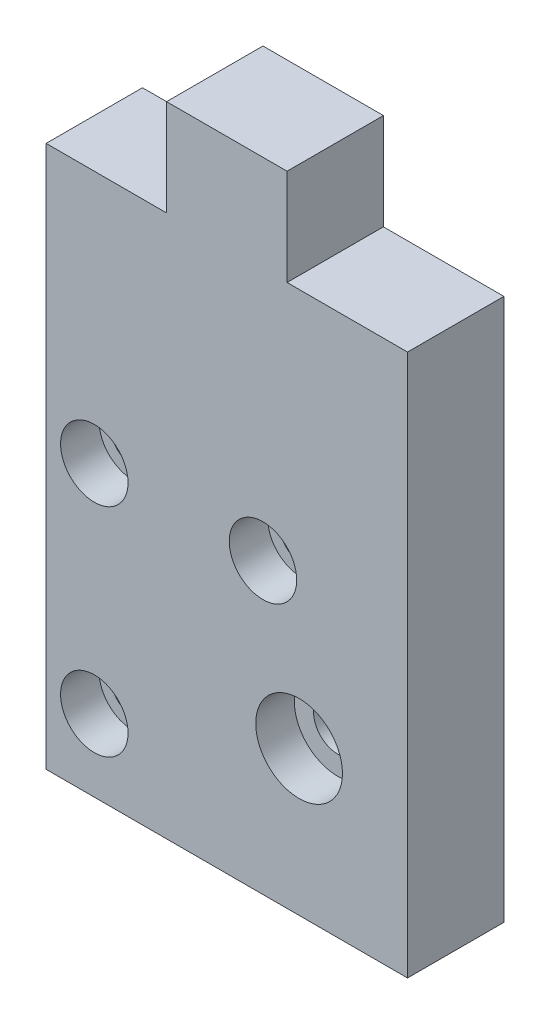
SolidWorks part; units mm, degrees
ref_plane "Front Plane" through (0, 0, 0) normal (0, 0, 1) x (1, 0, 0)
ref_plane "Top Plane" through (0, 0, 0) normal (0, 1, 0) x (1, 0, 0)
ref_plane "Right Plane" through (0, 0, 0) normal (1, 0, 0) x (0, 0, -1)
sketch "Sketch1" plane through (0, 0, 0) normal (0, 0, 1) x (1, 0, 0)
  line L0 (0, 57.15) -> (12.7, 57.15)
  line L1 (0, 0) -> (38.1, 0)
  line L5 (12.7, 57.15) -> (12.7, 67.31)
  line L6 (12.7, 67.31) -> (25.4, 67.31)
  line L7 (25.4, 67.31) -> (25.4, 57.15)
  line L8 (25.4, 57.15) -> (38.1, 57.15)
  line L9 (0, 57.15) -> (0, 0)
  line L10 (38.1, 57.15) -> (38.1, 0)
  line L11 (0, 74.3071) -> (10.16, 74.3071) construction
  line L12 (10.16, 74.3071) -> (10.16, 25.4) construction
  circle A0 centre (5.08, 7.62) radius 2.286
  circle A1 centre (5.08, 30.48) radius 2.286
  circle A2 centre (26.67, 15.24) radius 2.54
  circle A3 centre (22.86, 30.48) radius 2.286
  point P11 (29.21, 15.24)
  point P12 (24.13, 15.24)
  dimension "D3" = 7.62
  dimension "D5" = 4.572
  dimension "D6" = 4.572
  dimension "D8" = 29.21
  dimension "D9" = 12.7
  dimension "D10" = 10.16
  dimension "D13" = 17.78
  dimension "D14" = 4.572
  dimension "D16" = 15.24
  dimension "D1" = 38.1
  dimension "D2" = 5.08
  dimension "D4" = 24.13
  dimension "D7" = 22.86
  dimension "D11" = 10.16
  dimension "D12" = 25.4
  dimension "D15" = 5.08
extrude "Boss-Extrude1" add sketch "Sketch1" along normal blind 10.16
sketch "Sketch3" plane through (0, 0, 0) normal (0, 0, -1) x (-1, 0, 0)
  line L0 (-19.05, 67.31) -> (-19.05, 62.23) construction
  line L1 (-25.4, 67.31) -> (-12.7, 67.31) construction
  line L2 (-19.05, 62.23) -> (-12.7, 62.23) construction
  line L3 (-12.7, 67.31) -> (-12.7, 57.15) construction
  circle A0 centre (-19.05, 62.23) radius 1.27
  dimension "D1" = 2.54
sketch "Sketch7" plane through (0, 0, 10.16) normal (0, 0, 1) x (1, 0, 0)
  circle A0 centre (5.08, 30.48) radius 3.556
  circle A1 centre (22.86, 30.48) radius 3.556
  circle A2 centre (5.08, 7.62) radius 3.556
  circle A3 centre (26.67, 15.24) radius 4.572
  point P0 (5.08, 30.48)
  point P1 (5.08, 7.62)
  point P3 (22.86, 30.48)
  point P12 (26.67, 15.24)
  dimension "D1" = 7.112
  dimension "D2" = 7.112
  dimension "D3" = 7.112
  dimension "D4" = 9.144
extrude "Cut-Extrude1" cut sketch "Sketch7" against normal blind 4.064
extrude "Cut-Extrude2" cut sketch "Sketch3" against normal blind 0.508
